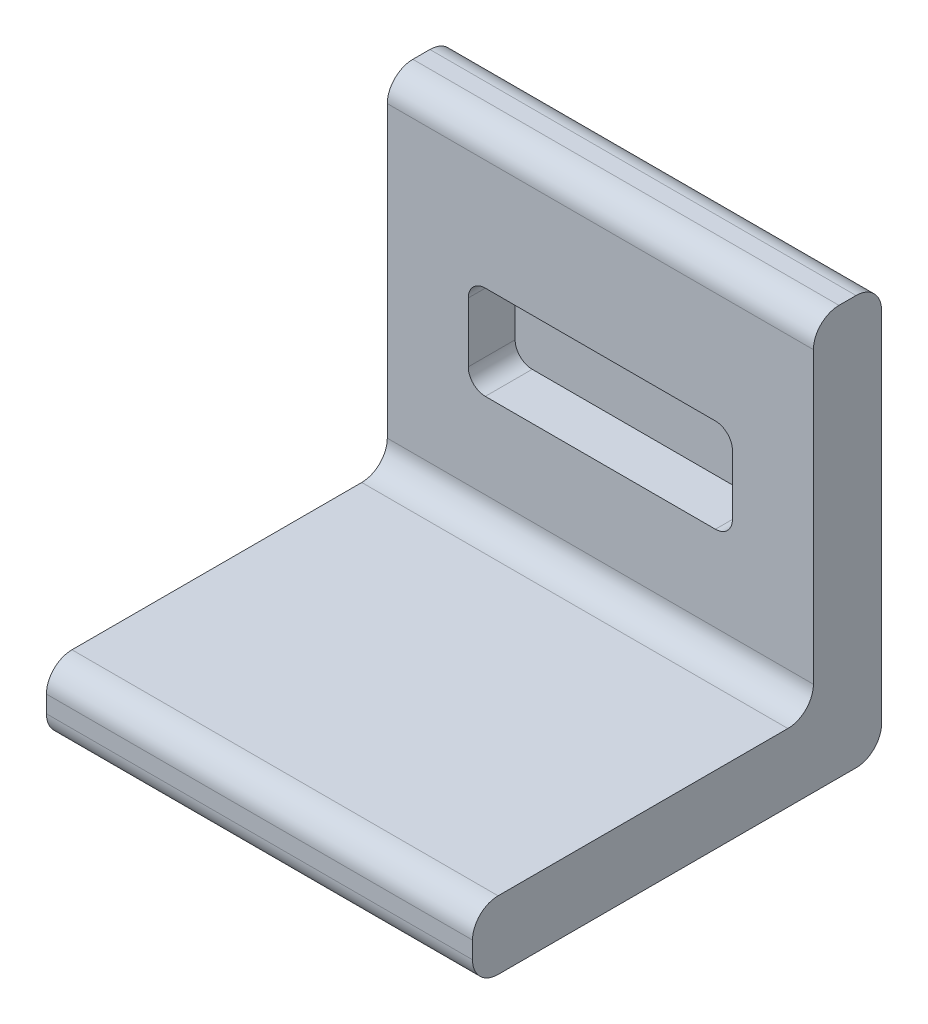
SolidWorks part; units mm, degrees
ref_plane "Front Plane" through (0, 0, 0) normal (0, 0, 1) x (1, 0, 0)
ref_plane "Top Plane" through (0, 0, 0) normal (0, 1, 0) x (1, 0, 0)
ref_plane "Right Plane" through (0, 0, 0) normal (1, 0, 0) x (0, 0, -1)
sketch "Sketch1" plane through (0, 0, 0) normal (0, 1, 0) x (1, 0, 0)
  line L0 (0, 0) -> (0, 46.6895) construction
  line L1 (-25, 40) -> (25, 40)
  line L2 (-25, 40) -> (-25, 0)
  line L3 (-25, 0) -> (25, 0)
  line L4 (25, 40) -> (25, 0)
  dimension "D1" = 50
  dimension "D2" = 40
extrude "Boss-Extrude1" add sketch "Sketch1" along normal blind 8
sketch "Sketch2" plane through (0, 0, -40) normal (0, 0, -1) x (-1, 0, 0)
  line L0 (-25, 8) -> (-25, 0) construction
  line L1 (-25, 48) -> (25, 48)
  line L2 (-25, 48) -> (-25, 0)
  line L3 (-25, 0) -> (25, 0)
  line L4 (25, 48) -> (25, 0)
  line L5 (25, 8) -> (25, 0) construction
  line L6 (-25, 8) -> (25, 8) construction
  dimension "D1" = 40
extrude "Boss-Extrude2" add sketch "Sketch2" along normal blind 8
sketch "Sketch3" plane through (0, 0, -40) normal (0, 0, 1) x (1, 0, 0)
  line L0 (0, 0) -> (0, 36.9321) construction
  line L1 (-15.5, 32) -> (15.5, 32)
  line L2 (-15.5, 32) -> (-15.5, 21)
  line L3 (-15.5, 21) -> (15.5, 21)
  line L4 (15.5, 32) -> (15.5, 21)
  line L5 (25, 8) -> (-25, 8) construction
  dimension "D1" = 13
  dimension "D2" = 31
  dimension "D3" = 11
extrude "Cut-Extrude1" cut sketch "Sketch3" against normal blind 5.5
fillet "Fillet1" radius 2 4 edges at (15.5, 21, -42.75) (15.5, 32, -42.75) (-15.5, 32, -42.75) (-15.5, 21, -42.75)
fillet "Fillet2" radius 3 6 edges at (0, 48, -48) (0, 0, 0) (0, 0, -48) (0, 8, -40) (0, 8, 0) (0, 48, -40)
